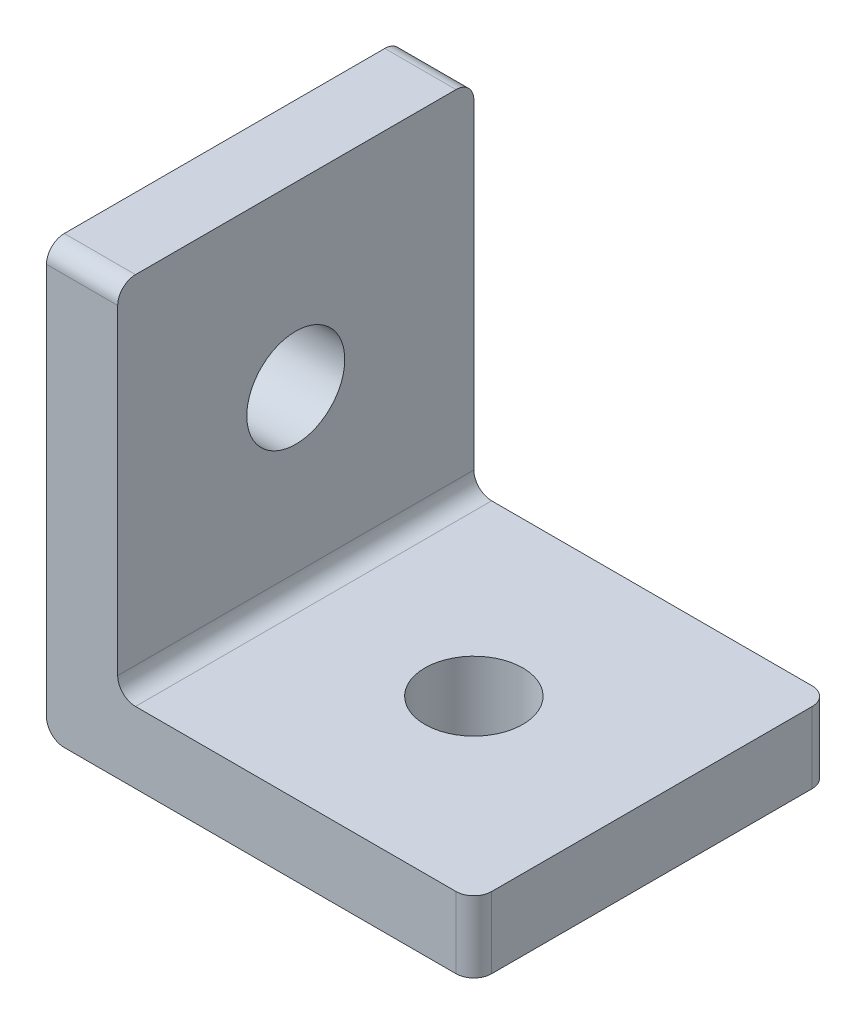
SolidWorks part; units mm, degrees
ref_plane "정면" through (0, 0, 0) normal (0, 0, 1) x (1, 0, 0)
ref_plane "윗면" through (0, 0, 0) normal (0, 1, 0) x (1, 0, 0)
ref_plane "우측면" through (0, 0, 0) normal (1, 0, 0) x (0, 0, -1)
sketch "스케치1" plane through (0, 0, 0) normal (0, 0, 1) x (1, 0, 0)
  line L1 (0, 0) -> (24, 0)
  line L2 (0, 0) -> (0, -4)
  line L3 (0, -4) -> (24, -4)
  line L4 (24, 0) -> (24, -4)
  line L5 (0, 0) -> (4, 0)
  line L6 (0, 0) -> (0, 20)
  line L7 (0, 20) -> (4, 20)
  line L8 (4, 0) -> (4, 20)
  point P8 (24, -2)
  dimension "D1" = 20
  dimension "D2" = 20
  dimension "D3" = 4
  dimension "D4" = 4
extrude "보스-돌출1" add sketch "스케치1" along normal blind 20 contours L4 L1 L2 L3 | L1 L8 L7 L6
sketch "스케치2" plane through (0, 0, 0) normal (0, 1, 0) x (1, 0, 0)
  line L0 (14, 0) -> (14, -20) construction
  line L1 (4, 0) -> (24, 0) construction
  line L2 (4, -20) -> (24, -20) construction
  line L3 (4, -10) -> (24, -10) construction
  line L4 (4, -20) -> (4, 0) construction
  line L5 (24, -20) -> (24, 0) construction
  circle A0 centre (14, -10) radius 2.75
  dimension "D1" = 5.5
extrude "컷-돌출1" cut sketch "스케치2" against normal blind 20
sketch "스케치3" plane through (4, 0, 0) normal (1, 0, 0) x (0, 0, -1)
  line L0 (-20, 10) -> (0, 10) construction
  line L1 (-20, 0) -> (-20, 20) construction
  line L2 (0, 0) -> (0, 20) construction
  line L3 (-10, 20) -> (-10, 0) construction
  line L4 (-20, 20) -> (0, 20) construction
  line L5 (-20, 0) -> (0, 0) construction
  circle A0 centre (-10, 10) radius 2.75
  dimension "D1" = 5.5
extrude "컷-돌출2" cut sketch "스케치3" against normal blind 20
fillet "필렛1" radius 1 6 edges at (2, 20, 0) (2, 20, 20) (24, -2, 0) (24, -2, 20) (4, 0, 10) (0, -4, 10)
